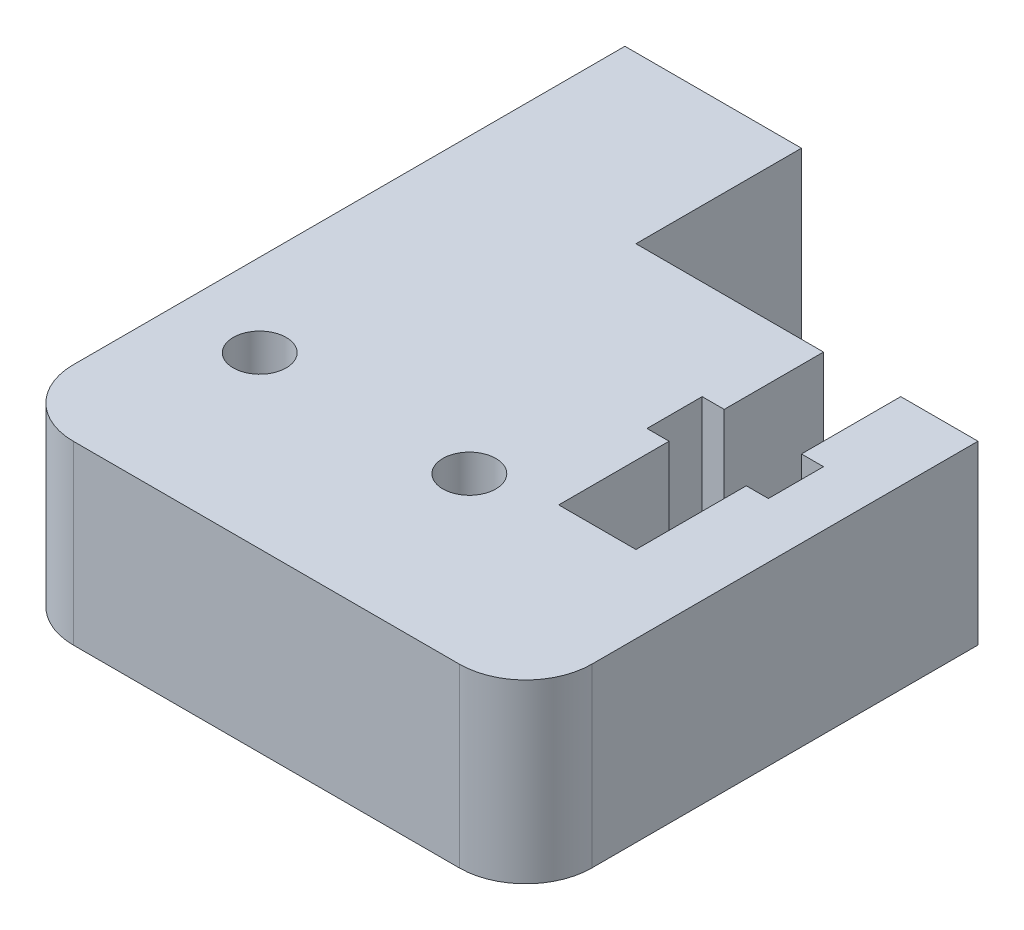
SolidWorks part; units mm, degrees
ref_plane "Front Plane" through (0, 0, 0) normal (0, 0, 1) x (1, 0, 0)
ref_plane "Top Plane" through (0, 0, 0) normal (0, 1, 0) x (1, 0, 0)
ref_plane "Right Plane" through (0, 0, 0) normal (1, 0, 0) x (0, 0, -1)
sketch "Sketch1" plane through (0, 0, 0) normal (0, 1, 0) x (1, 0, 0)
  line L0 (26.4198, 30.4696) -> (26.4198, 25.9696)
  line L1 (26.4198, 25.9696) -> (25.4198, 25.9696)
  line L2 (25.4198, 25.9696) -> (25.4198, 23.4696)
  line L3 (25.4198, 23.4696) -> (26.4198, 23.4696)
  line L4 (26.4198, 23.4696) -> (26.4198, 18.4696)
  line L5 (26.4198, 18.4696) -> (29.9198, 18.4696)
  line L6 (29.9198, 18.4696) -> (29.9198, 23.4696)
  line L7 (29.9198, 23.4696) -> (30.9198, 23.4696)
  line L8 (30.9198, 23.4696) -> (30.9198, 25.9696)
  line L9 (30.9198, 25.9696) -> (29.9198, 25.9696)
  line L10 (29.9198, 25.9696) -> (29.9198, 30.4696)
  line L11 (29.9198, 30.4696) -> (33.4198, 30.4696)
  line L12 (33.4198, 30.4696) -> (33.4198, 12.9696)
  line L13 (30.4198, 9.9696) -> (12.9198, 9.9696)
  line L14 (9.9198, 12.9696) -> (9.9198, 30.4696)
  line L15 (9.9198, 30.4696) -> (9.9198, 37.9696)
  line L16 (9.9198, 37.9696) -> (17.9198, 37.9696)
  line L17 (17.9198, 37.9696) -> (17.9198, 30.4696)
  line L18 (17.9198, 30.4696) -> (26.4198, 30.4696)
  arc A0 (30.4198, 9.9696) -> (33.4198, 12.9696) centre (30.4198, 12.9696) ccw
  arc A1 (9.9198, 12.9696) -> (12.9198, 9.9696) centre (12.9198, 12.9696) ccw
  circle A2 centre (23.1698, 17.6696) radius 1.2
  circle A3 centre (13.6698, 17.6696) radius 1.2
extrude "Extrude1" add sketch "Sketch1" along normal blind 8
sketch "Sketch2" plane through (0, 0, -18.4696) normal (0, 0, -1) x (-1, 0, 0)
  line L0 (-26.4198, 8) -> (-29.9198, 0)
  circle A0 centre (-28.1698, 4) radius 1
  dimension "D1" = 2
extrude "Extrude2" cut sketch "Sketch2" against normal blind 1 contours A0
